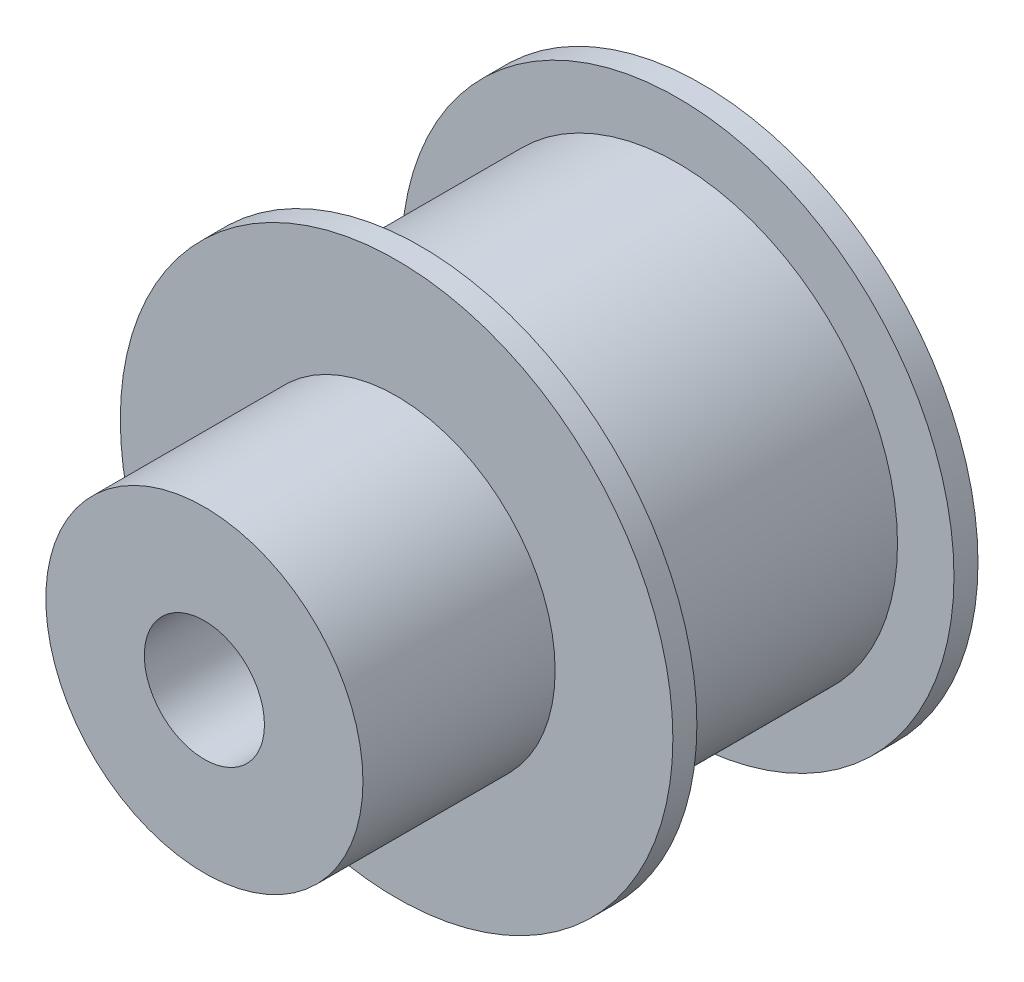
SolidWorks part; units mm, degrees
ref_plane "Спереди" through (0, 0, 0) normal (0, 0, 1) x (1, 0, 0)
ref_plane "Сверху" through (0, 0, 0) normal (0, 1, 0) x (1, 0, 0)
ref_plane "Справа" through (0, 0, 0) normal (1, 0, 0) x (0, 0, -1)
sketch "Эскиз1" plane through (0, 0, 0) normal (0, 0, 1) x (1, 0, 0)
  circle A0 centre (0, 0) radius 11.5
  dimension "D1" = 23
extrude "Бобышка-Вытянуть1" add sketch "Эскиз1" along normal blind 1
sketch "Эскиз2" plane through (0, 0, 1) normal (0, 0, 1) x (1, 0, 0)
  circle A0 centre (0, 0) radius 9.15
  dimension "D1" = 18.3
extrude "Бобышка-Вытянуть2" add sketch "Эскиз2" along normal blind 10.7
sketch "Эскиз3" plane through (0, 0, 11.7) normal (0, 0, 1) x (1, 0, 0)
  circle A0 centre (0, 0) radius 11.5
  dimension "D1" = 23
extrude "Бобышка-Вытянуть3" add sketch "Эскиз3" along normal blind 1
sketch "Эскиз4" plane through (0, 0, 12.7) normal (0, 0, 1) x (1, 0, 0)
  circle A0 centre (0, 0) radius 6.6
  dimension "D1" = 13.2
extrude "Бобышка-Вытянуть4" add sketch "Эскиз4" along normal blind 8
sketch "Эскиз5" plane through (0, 0, 20.7) normal (0, 0, 1) x (1, 0, 0)
  circle A0 centre (0, 0) radius 2.5
  dimension "D1" = 5
extrude "Вырез-Вытянуть1" cut sketch "Эскиз5" against normal through all
ref_plane "Плоскость1" through (0, 0, 6.35) normal (0, 0, -1) x (-1, 0, 0)
